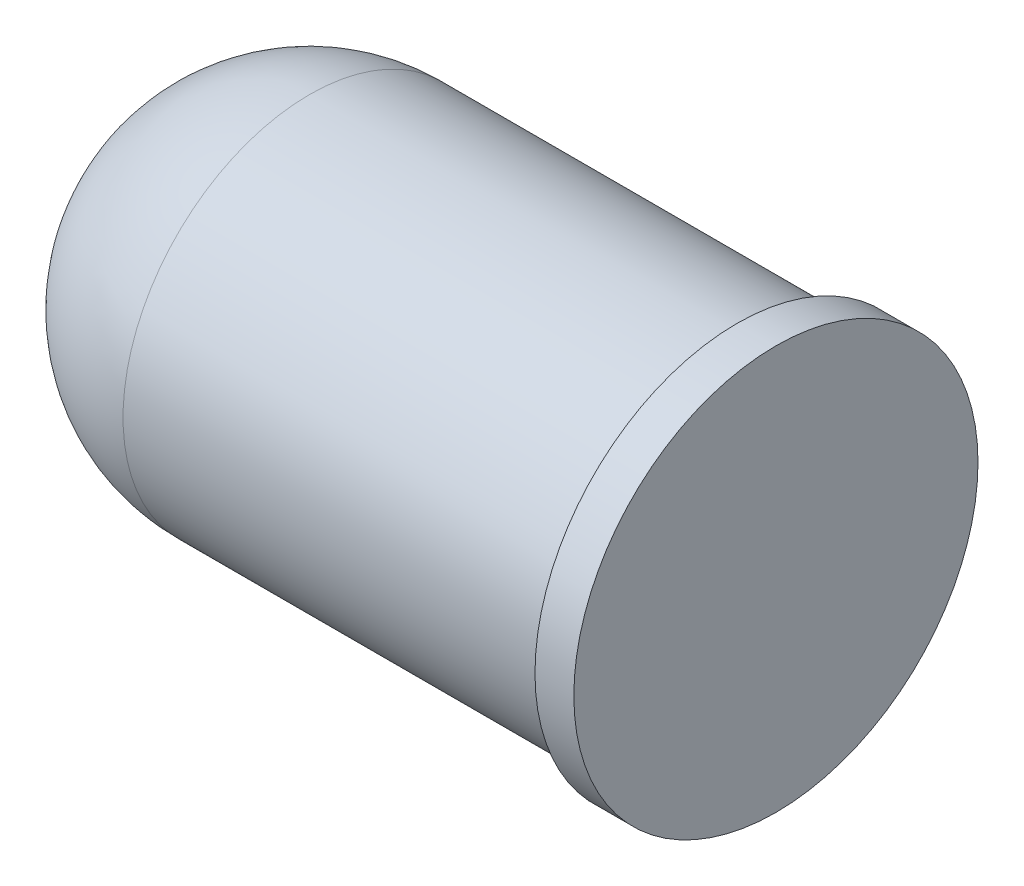
SolidWorks part; units mm, degrees
ref_plane "Plan de face" through (0, 0, 0) normal (0, 0, 1) x (1, 0, 0)
ref_plane "Plan de dessus" through (0, 0, 0) normal (0, 1, 0) x (1, 0, 0)
ref_plane "Plan de droite" through (0, 0, 0) normal (1, 0, 0) x (0, 0, -1)
sketch "Esquisse1" plane through (0, 0, 0) normal (0, 0, 1) x (1, 0, 0)
  line L0 (-6.7768, 0) -> (1.5223, 0) construction
  line L1 (0, 0) -> (-8.4, 0)
  line L2 (0, 0) -> (0, 2.6)
  line L3 (-0.5, 2.4) -> (-6, 2.4)
  line L7 (0, 2.6) -> (-0.5, 2.6)
  line L8 (-0.5, 2.4) -> (-0.5, 2.6)
  arc A0 (-8.4, 0) -> (-6, 2.4) centre (-6, 0) cw
  dimension "D1" = 4.8
  dimension "D2" = 5.2
  dimension "D3" = 0.5
  dimension "D4" = 8.4
revolve "Révolution1" add sketch "Esquisse1" angle 360 about L0
